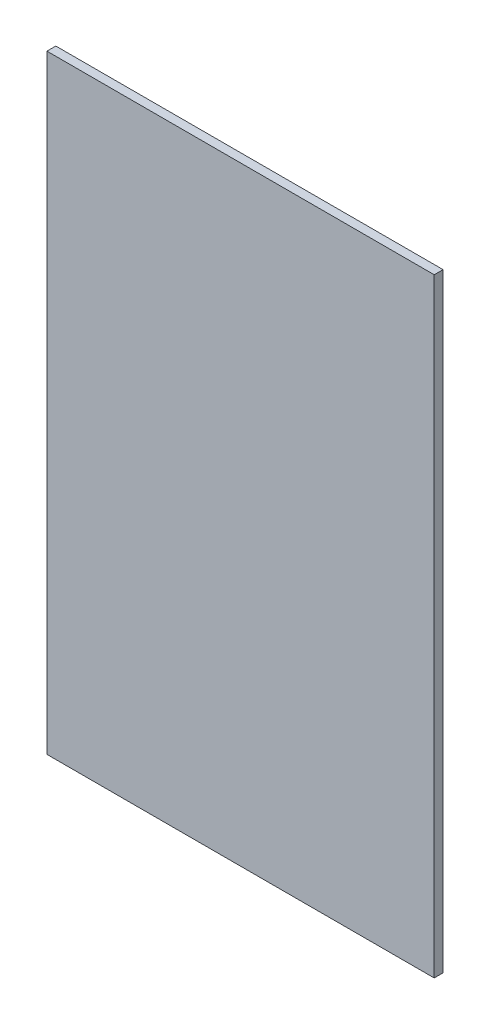
SolidWorks part; units mm, degrees
ref_plane "Front Plane" through (0, 0, 0) normal (0, 0, 1) x (1, 0, 0)
ref_plane "Top Plane" through (0, 0, 0) normal (0, 1, 0) x (1, 0, 0)
ref_plane "Right Plane" through (0, 0, 0) normal (1, 0, 0) x (0, 0, -1)
sketch "Sketch1" plane through (0, 0, 0) normal (0, 0, 1) x (1, 0, 0)
  line L1 (-65.5, -103) -> (65.5, -103)
  line L2 (-65.5, -103) -> (-65.5, 103)
  line L3 (-65.5, 103) -> (65.5, 103)
  line L4 (65.5, -103) -> (65.5, 103)
  line L5 (-65.5, -103) -> (65.5, 103) construction
  line L6 (-65.5, 103) -> (65.5, -103) construction
  point P0 (0, 0)
  dimension "D1" = 131
  dimension "D2" = 206
extrude "Boss-Extrude1" add sketch "Sketch1" along normal blind 3
